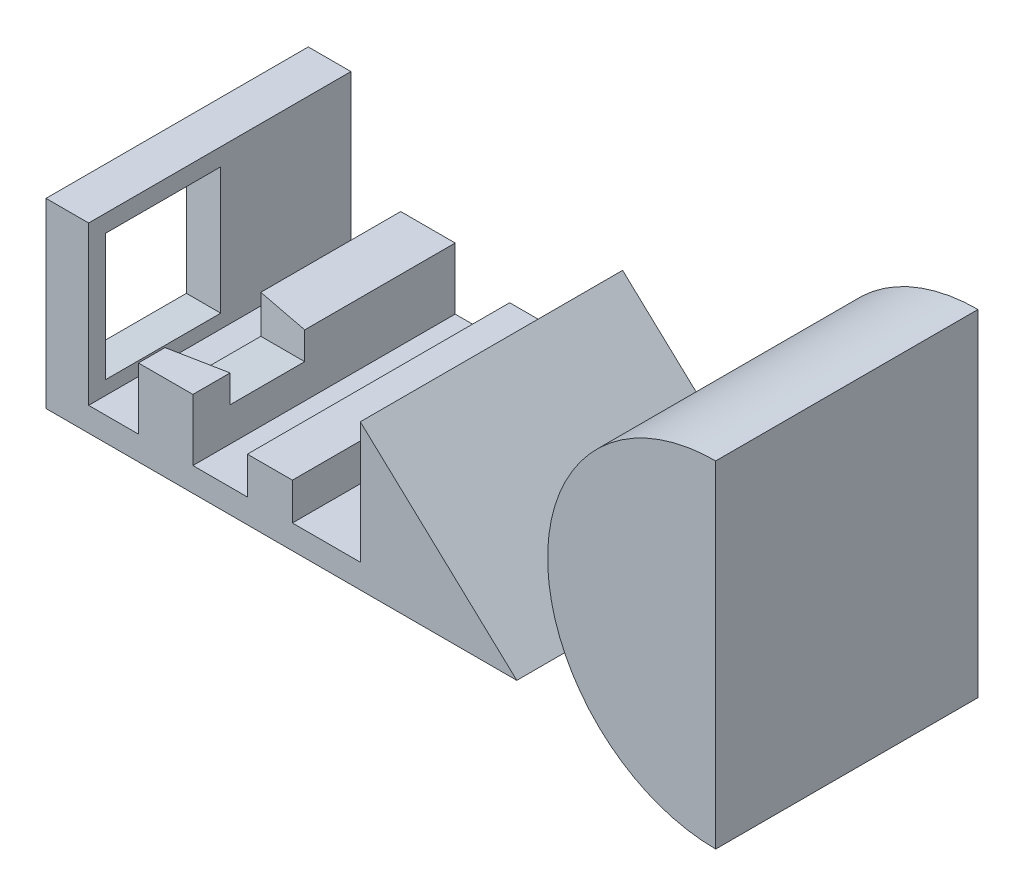
SolidWorks part; units mm, degrees
ref_plane "Front Plane" through (0, 0, 0) normal (0, 0, 1) x (1, 0, 0)
ref_plane "Top Plane" through (0, 0, 0) normal (0, 1, 0) x (1, 0, 0)
ref_plane "Right Plane" through (0, 0, 0) normal (1, 0, 0) x (0, 0, -1)
sketch "Sketch1" plane through (0, 0, 0) normal (0, 0, 1) x (1, 0, 0)
  line L0 (0, 0) -> (0, 264.4383)
  line L1 (0, 264.4383) -> (61.9508, 264.4383)
  line L2 (61.9508, 264.4383) -> (61.9508, 34.9907)
  line L3 (61.9508, 34.9907) -> (134.2268, 34.9907)
  line L4 (134.2268, 34.9907) -> (134.2268, 124.4753)
  line L5 (134.2268, 124.4753) -> (213.3862, 124.4753)
  line L6 (213.3862, 124.4753) -> (213.3862, 34.9907)
  line L7 (213.3862, 34.9907) -> (292.5456, 34.9907)
  line L8 (292.5456, 34.9907) -> (292.5456, 88.9109)
  line L9 (292.5456, 88.9109) -> (357.9381, 88.9109)
  line L10 (357.9381, 88.9109) -> (357.9381, 34.9907)
  line L11 (357.9381, 34.9907) -> (456.6006, 34.9907)
  line L12 (456.6006, 34.9907) -> (456.6006, 211.6653)
  line L13 (456.6006, 211.6653) -> (683.9372, 0)
  line L14 (683.9372, 0) -> (0, 0)
  line L15 (972.8798, 420.6031) -> (972.8798, -67.7629)
  arc A0 (972.8798, 420.6031) -> (972.8798, -67.7629) centre (972.8798, 176.4201) ccw
extrude "Boss-Extrude1" add sketch "Sketch1" along normal mid plane 381
sketch "Sketch2" plane through (0, 0, 0) normal (-1, 0, 0) x (0, 0, 1)
  line L1 (-13.4183, 251.2147) -> (177.9167, 251.2147)
  line L2 (-13.4183, 251.2147) -> (-13.4183, 42.9826)
  line L3 (-13.4183, 42.9826) -> (177.9167, 42.9826)
  line L4 (177.9167, 251.2147) -> (177.9167, 42.9826)
extrude "Cut-Extrude1" cut sketch "Sketch2" against normal blind 254 draft 11
